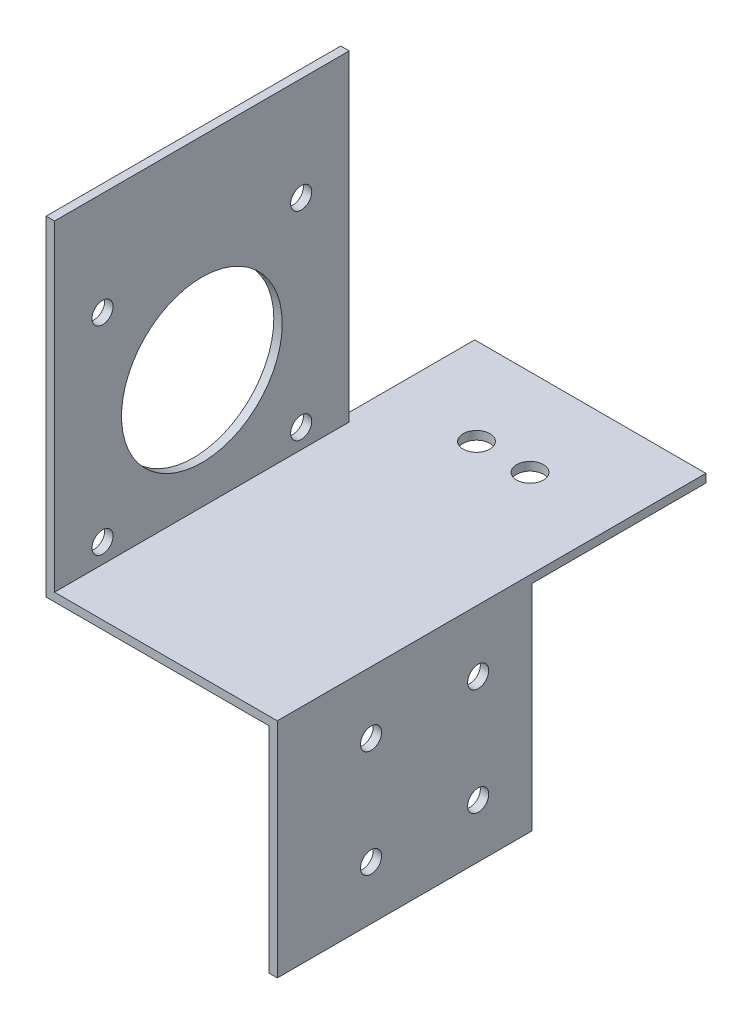
SolidWorks part; units mm, degrees
ref_plane "Front Plane" through (0, 0, 0) normal (0, 0, 1) x (1, 0, 0)
ref_plane "Top Plane" through (0, 0, 0) normal (0, 1, 0) x (1, 0, 0)
ref_plane "Right Plane" through (0, 0, 0) normal (1, 0, 0) x (0, 0, -1)
sketch "Sketch1" plane through (0, 0, 0) normal (1, 0, 0) x (0, 0, -1)
  line L1 (-34.925, -25.4) -> (34.925, -25.4)
  line L2 (-34.925, -25.4) -> (-34.925, 25.4)
  line L3 (-34.925, 25.4) -> (34.925, 25.4)
  line L4 (34.925, -25.4) -> (34.925, 25.4)
  line L5 (-34.925, -25.4) -> (34.925, 25.4) construction
  line L6 (-34.925, 25.4) -> (34.925, -25.4) construction
  point P0 (0, 0)
  dimension "D1" = 69.85
  dimension "D2" = 50.8
extrude "Boss-Extrude1" add sketch "Sketch1" against normal blind 2
sketch "Sketch2" plane through (0, 25.4, 0) normal (0, 1, 0) x (1, 0, 0)
  line L0 (-2, -34.925) -> (0, -34.925) construction
  line L1 (0, 34.925) -> (-54.8, 34.925)
  line L2 (0, 34.925) -> (0, -34.925)
  line L3 (0, -34.925) -> (-54.8, -34.925)
  line L4 (-54.8, 34.925) -> (-54.8, -34.925)
  point P7 (-1, -34.925)
  dimension "D1" = 54.8
extrude "Boss-Extrude2" add sketch "Sketch2" along normal blind 2
sketch "Sketch3" plane through (0, 27.4, 0) normal (0, 1, 0) x (1, 0, 0)
  line L0 (-54.8, -34.925) -> (0, -34.925) construction
  line L1 (-54.8, 34.925) -> (-52.8, 34.925)
  line L2 (-54.8, 34.925) -> (-54.8, -34.925)
  line L3 (-54.8, -34.925) -> (-52.8, -34.925)
  line L4 (-52.8, 34.925) -> (-52.8, -34.925)
  dimension "D1" = 2
extrude "Boss-Extrude3" add sketch "Sketch3" along normal blind 76.2
sketch "Sketch4" plane through (-52.8, 0, 0) normal (1, 0, 0) x (0, 0, -1)
  line L1 (-34.925, 27.4) -> (34.925, 27.4) construction
  line L2 (-23.55, 79.118) -> (23.55, 79.118) construction
  line L3 (23.55, 79.118) -> (23.55, 32.018) construction
  line L4 (23.55, 32.018) -> (-23.55, 32.018) construction
  line L5 (-23.55, 32.018) -> (-23.55, 79.118) construction
  line L6 (0, 55.568) -> (0, 103.6) construction
  line L7 (-34.925, 103.6) -> (34.925, 103.6) construction
  circle A0 centre (0, 55.568) radius 19.05
  circle A1 centre (23.55, 79.118) radius 2.5
  circle A2 centre (-23.55, 79.118) radius 2.5
  circle A3 centre (-23.55, 32.018) radius 2.5
  circle A4 centre (23.55, 32.018) radius 2.5
  dimension "D3" = 38.1
  dimension "D8" = 5
  dimension "D2" = 28.168
  dimension "D4" = 23.55
  dimension "D5" = 23.55
  dimension "D6" = 23.55
  dimension "D7" = 23.55
extrude "Cut-Extrude1" cut sketch "Sketch4" against normal through all
sketch "Sketch5" plane through (0, 0, 0) normal (1, 0, 0) x (0, 0, -1)
  line L0 (-34.925, -25.4) -> (34.925, -25.4) construction
  line L1 (34.925, 27.4) -> (25.4, 27.4)
  line L2 (34.925, 27.4) -> (34.925, -25.4)
  line L3 (34.925, -25.4) -> (25.4, -25.4)
  line L4 (25.4, 27.4) -> (25.4, -25.4)
  line L5 (-12.7, 12.7) -> (12.7, 12.7) construction
  line L6 (12.7, 12.7) -> (12.7, -12.7) construction
  line L7 (12.7, -12.7) -> (-12.7, -12.7) construction
  line L8 (-12.7, -12.7) -> (-12.7, 12.7) construction
  circle A0 centre (-12.7, 12.7) radius 2.5
  circle A1 centre (12.7, 12.7) radius 2.5
  circle A2 centre (12.7, -12.7) radius 2.5
  circle A3 centre (-12.7, -12.7) radius 2.5
  dimension "D6" = 5
  dimension "D1" = 25.4
  dimension "D2" = 12.7
  dimension "D3" = 12.7
  dimension "D4" = 12.7
  dimension "D5" = 12.7
extrude "Cut-Extrude2" cut sketch "Sketch5" against normal blind 76.2
sketch "Sketch6" plane through (0, 0, -25.4) normal (0, 0, -1) x (-1, 0, 0)
  line L1 (0, 27.4) -> (54.8, 27.4)
  line L2 (0, 27.4) -> (0, 25.4)
  line L3 (0, 25.4) -> (54.8, 25.4)
  line L4 (54.8, 27.4) -> (54.8, 25.4)
extrude "Boss-Extrude4" add sketch "Sketch6" along normal blind 41.275
sketch "Sketch7" plane through (0, 27.4, 0) normal (0, 1, 0) x (1, 0, 0)
  line L0 (-54.8, 66.675) -> (0, 66.675) construction
  line L1 (-21.05, 46.0375) -> (-33.75, 46.0375) construction
  line L2 (-27.4, 66.675) -> (-27.4, 46.0375) construction
  circle A0 centre (-33.75, 46.0375) radius 3.175
  circle A1 centre (-21.05, 46.0375) radius 3.175
  point P6 (-27.4, 46.0375)
  point P7 (-27.4, 66.675)
  dimension "D1" = 6.35
  dimension "D2" = 20.6375
  dimension "D3" = 6.35
extrude "Cut-Extrude3" cut sketch "Sketch7" against normal through all
